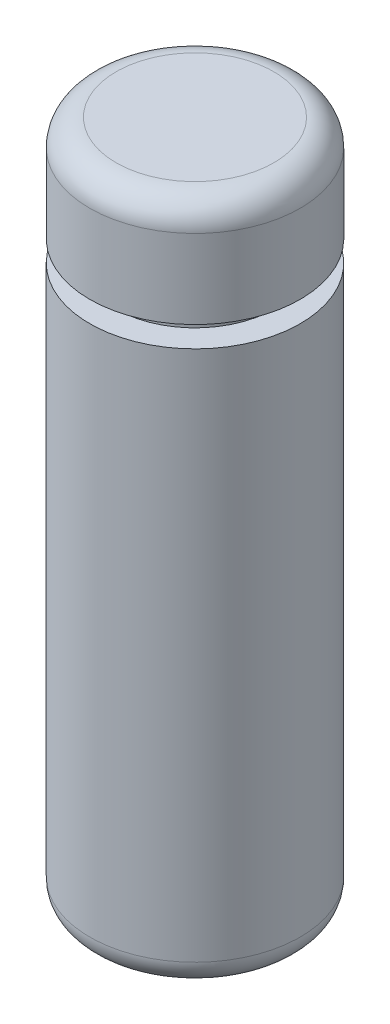
SolidWorks part; units mm, degrees
ref_plane "Plan de face" through (0, 0, 0) normal (0, 0, 1) x (1, 0, 0)
ref_plane "Plan de dessus" through (0, 0, 0) normal (0, 1, 0) x (1, 0, 0)
ref_plane "Plan de droite" through (0, 0, 0) normal (1, 0, 0) x (0, 0, -1)
sketch "Esquisse2" plane through (0, 0, 0) normal (0, 0, 1) x (1, 0, 0)
  line L0 (0, 0) -> (0, 23.661) construction
  line L1 (0, 26) -> (4, 26)
  line L2 (4, 26) -> (4, 0)
  line L3 (4, 0) -> (0, 0)
  line L4 (0, 0) -> (0, 26)
  dimension "D1" = 8
  dimension "D2" = 26
revolve "Révolution1" add sketch "Esquisse2" angle 360 about L0
fillet "Congé2" radius 1 2 edges at (0, 26, -4) (0, 0, -4)
sketch "Esquisse3" plane through (0, 0, 0) normal (0, 0, 1) x (1, 0, 0)
  line L0 (3, 26) -> (-3, 26) construction
  line L1 (-3.0232, 22) -> (-4.4405, 22)
  line L2 (-3.0232, 22) -> (-3.0232, 21.2)
  line L3 (-3.0232, 21.2) -> (-4.4405, 21.2)
  line L4 (-4.4405, 22) -> (-4.4405, 21.2)
  dimension "D1" = 0.8
  dimension "D2" = 4
revolve "Enlèvement de matière-Révolution1" cut sketch "Esquisse3" angle 360 about axis through (0, 0, 0) along (0, -1, 0)
